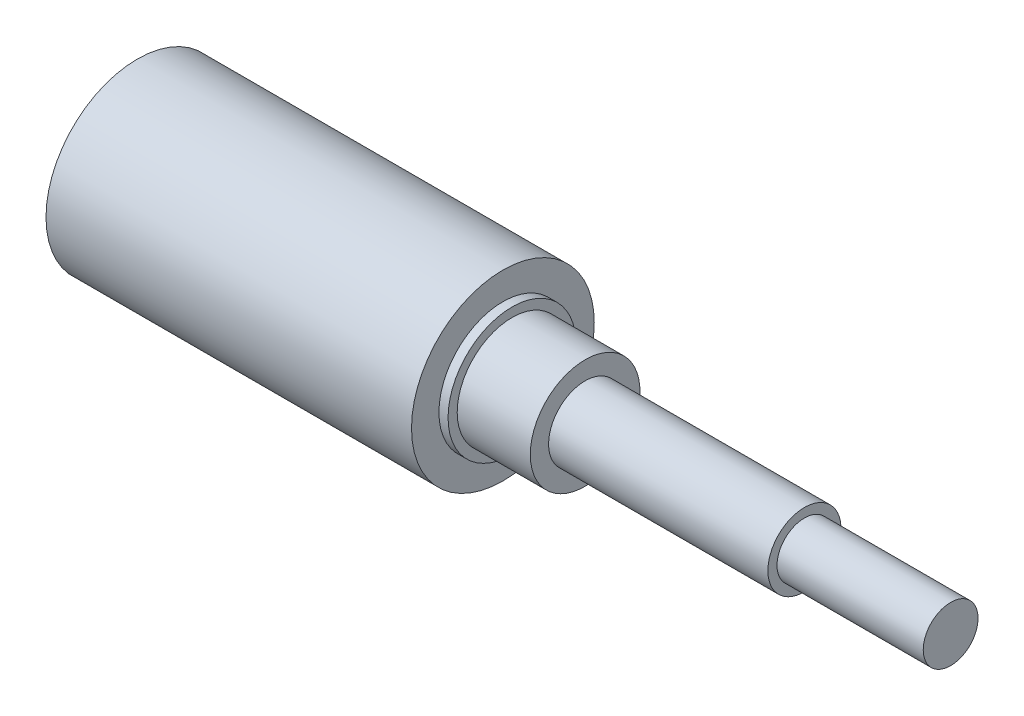
SolidWorks part; units mm, degrees
material "Brass"
ref_plane "Front Plane" through (0, 0, 0) normal (0, 0, 1) x (1, 0, 0)
ref_plane "Top Plane" through (0, 0, 0) normal (0, 1, 0) x (1, 0, 0)
ref_plane "Right Plane" through (0, 0, 0) normal (1, 0, 0) x (0, 0, -1)
sketch "Sketch1" plane through (0, 0, 0) normal (0, 0, 1) x (1, 0, 0)
  line L0 (0, 0) -> (44.5, 0)
  line L1 (44.5, 0) -> (44.5, 1.5)
  line L2 (36.5, 2) -> (24.5, 2)
  line L3 (24.5, 2) -> (24.5, 3)
  line L4 (24.5, 3) -> (20.5, 3)
  line L5 (20, 3.5) -> (20, 5)
  line L6 (20, 5) -> (0, 5)
  line L7 (0, 5) -> (0, 0)
  line L8 (20, 3.5) -> (20.5, 3.5)
  line L9 (20.5, 3.5) -> (20.5, 3)
  line L10 (36.5, 2) -> (36.5, 1.5)
  line L11 (36.5, 1.5) -> (44.5, 1.5)
  dimension "D1" = 4
  dimension "D2" = 5
  dimension "D3" = 0.5
  dimension "D4" = 3
  dimension "D5" = 20
  dimension "D6" = 20
  dimension "D7" = 2
  dimension "D8" = 1.5
  dimension "D9" = 8
revolve "Revolve1" add sketch "Sketch1" angle 360 about L0
